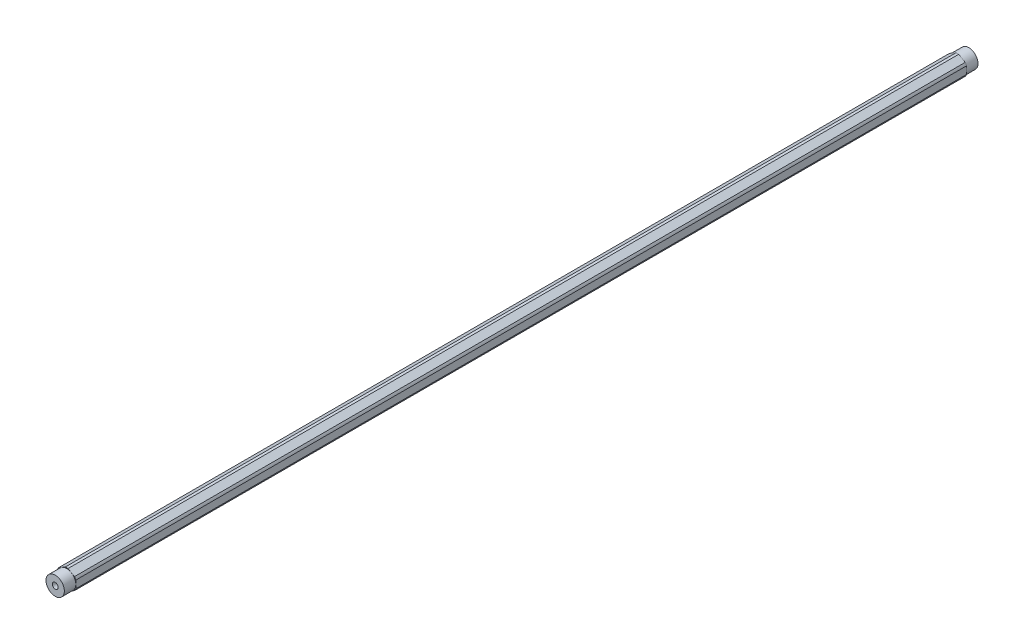
SolidWorks part; units mm, degrees
material "7075-T6 (SN)"
ref_plane "Front Plane" through (0, 0, 0) normal (0, 0, 1) x (1, 0, 0)
ref_plane "Top Plane" through (0, 0, 0) normal (0, 1, 0) x (1, 0, 0)
ref_plane "Right Plane" through (0, 0, 0) normal (1, 0, 0) x (0, 0, -1)
sketch "Sketch2" plane through (0, 0, 0) normal (0, 0, 1) x (1, 0, 0)
  line L1 (0, 7.3323) -> (-6.35, 3.6662)
  line L2 (-6.35, 3.6662) -> (-6.35, -3.6662)
  line L3 (-6.35, -3.6662) -> (0, -7.3323)
  line L4 (0, -7.3323) -> (6.35, -3.6662)
  line L5 (6.35, -3.6662) -> (6.35, 3.6662)
  line L6 (6.35, 3.6662) -> (0, 7.3323)
  circle A0 centre (0, 0) radius 6.35 construction
  circle A2 centre (0, 0) radius 2.0193
  circle A3 centre (0, 0) radius 6.858
  dimension "D1" = 12.7
  dimension "D2" = 13.716
  dimension "D3" = 4.0386
extrude "Boss-Extrude1" add sketch "Sketch2" along normal mid plane 615.95 contours L5 A3 L6 L1 L2 L3 L4 A2
sketch "Sketch7" plane through (0, 0, 307.975) normal (0, 0, 1) x (1, 0, 0)
  circle A0 centre (0, 0) radius 6.35
  dimension "D1" = 12.7
extrude "Boss-Extrude2" add sketch "Sketch7" along normal blind 7.9375
mirror "Mirror1" about plane through (0, 0, 0) normal (0, 0, 1) of "Boss-Extrude2"
hole_wizard "#10-32 Tapped Hole2" positions "3DSketch1" profile "Sketch6" tap size "#10-32" standard "ANSI Inch"
sketch3d "3DSketch1"
  line L0 (0, 0, 315.9125) -> (0, 0, 307.975) construction
  line L1 (0, 0, -315.9125) -> (0, 0, -307.975) construction
  point P14 (0, 0, 315.9125)
  point P18 (0, 0, -315.9125)
sketch "Sketch6" plane through (0, 0, 315.9125) normal (1, 0, 0) x (0, -1, 0)
  line L0 (0, 0) -> (0, 17.5608)
  line L1 (0, 17.5608) -> (2.0193, 16.3474)
  line L2 (2.0193, 16.3474) -> (2.0193, 0)
  line L5 (2.0193, 0) -> (0, 0)
  line L10 (0, 17.5608) -> (-2.0193, 16.3474) construction
  line L11 (0, -6.35) -> (0, 107.95) construction
  dimension "Tap Drill Dia." = 4.0386
  dimension "Tap Drill Depth" = 16.3474
  dimension "Drill Angle" = 118
cosmetic thread "Hole Thread1" parameters "D1"=13.97, "D2"=4.826
cosmetic thread "Hole Thread2" parameters "D1"=13.97, "D2"=4.826
